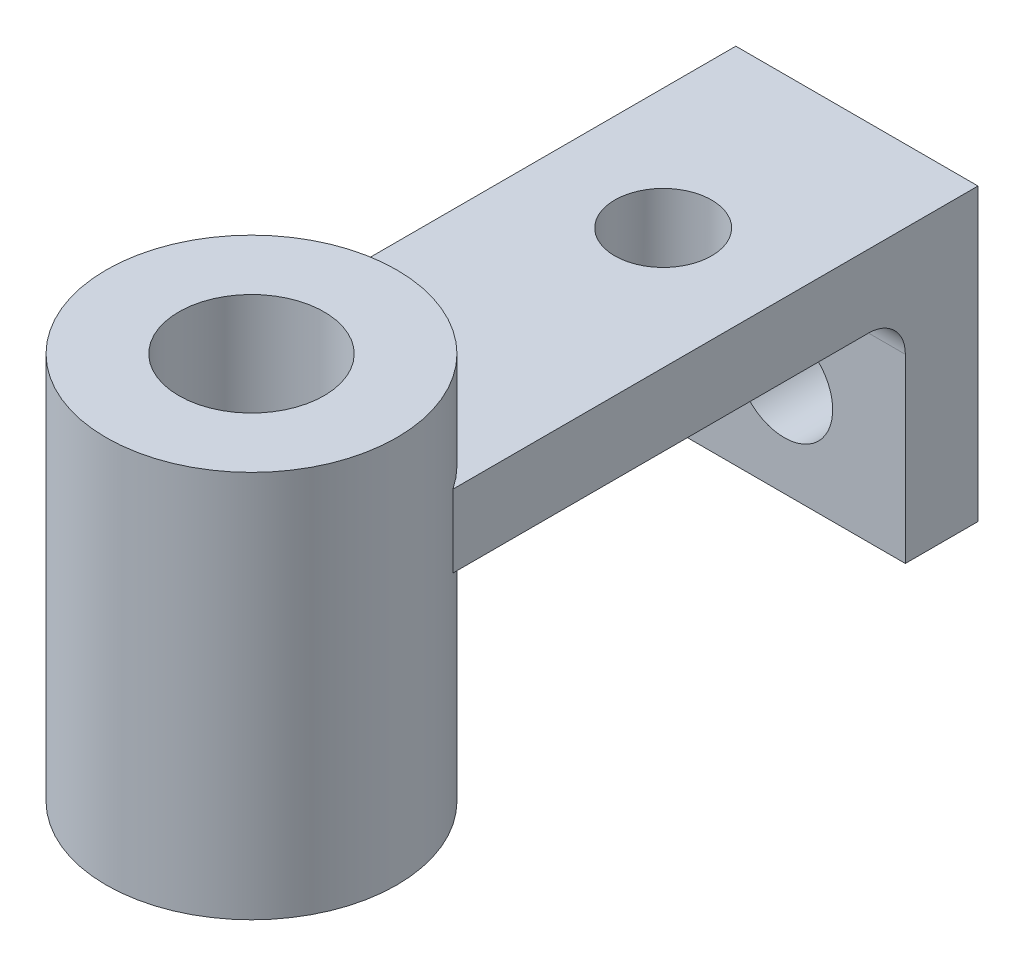
SolidWorks part; units mm, degrees
ref_plane "Alzado" through (0, 0, 0) normal (0, 0, 1) x (1, 0, 0)
ref_plane "Planta" through (0, 0, 0) normal (0, 1, 0) x (1, 0, 0)
ref_plane "Vista lateral" through (0, 0, 0) normal (1, 0, 0) x (0, 0, -1)
sketch "Croquis3" plane through (0, 0, 0) normal (1, 0, 0) x (0, 0, -1)
  line L0 (39.6875, 4.7625) -> (39.6875, -33.3375)
  line L1 (-39.6875, 4.7625) -> (39.6875, 4.7625)
  line L2 (-39.6875, 4.7625) -> (-39.6875, -4.7625)
  line L5 (-39.6875, 4.7625) -> (39.6875, -4.7625) construction
  line L6 (-39.6875, -4.7625) -> (39.6875, 4.7625) construction
  line L7 (39.6875, -33.3375) -> (30.1625, -33.3375)
  line L8 (30.1625, -33.3375) -> (30.1625, -9.5885)
  line L9 (25.3365, -4.7625) -> (-39.6875, -4.7625)
  arc A0 (30.1625, -9.5885) -> (25.3365, -4.7625) centre (25.3365, -9.5885) ccw
  point P0 (0, 0)
  dimension "D5" = 4.826
  dimension "D1" = 9.525
  dimension "D2" = 79.375
  dimension "D3" = 38.1
  dimension "D4" = 9.525
extrude "Saliente-Extruir1" add sketch "Croquis3" along normal blind 31.75 contours L9 L2 L1 L0 L7 L8 A0
sketch "Croquis5" plane through (0, 0, -39.6875) normal (0, 0, -1) x (-1, 0, 0)
  line L0 (-15.875, -16.1629) -> (-15.875, -35.7571) construction
  line L1 (-22.6938, -20.6375) -> (2.7786, -20.6375) construction
  line L2 (-31.75, -33.3375) -> (0, -33.3375) construction
  line L3 (0, 4.7625) -> (0, -33.3375) construction
  circle A0 centre (-15.875, -20.6375) radius 6.35
  dimension "D3" = 12.7
  dimension "D1" = 12.7
  dimension "D2" = 15.875
extrude "Cortar-Extruir1" cut sketch "Croquis5" against normal up to next
sketch "Croquis6" plane through (0, 4.7625, 0) normal (0, 1, 0) x (1, 0, 0)
  line L0 (31.75, -39.6875) -> (0, -39.6875) construction
  line L1 (0, -39.6875) -> (0, 39.6875) construction
  circle A0 centre (15.875, 14.2875) radius 6.35
  dimension "D3" = 12.7
  dimension "D1" = 53.975
  dimension "D2" = 15.875
extrude "Cortar-Extruir2" cut sketch "Croquis6" against normal up to next
sketch "Croquis7" plane through (0, 4.7625, 0) normal (0, 1, 0) x (1, 0, 0)
  line L0 (15.875, -43.3287) -> (15.875, 41.346) construction
  line L1 (31.75, -39.6875) -> (0, -39.6875) construction
  circle A0 centre (15.875, -39.6875) radius 19.05
  dimension "D1" = 38.1
extrude "Saliente-Extruir2" add sketch "Croquis7" along normal blind 12.7 and the other way blind 38.1
sketch "Croquis8" plane through (0, 17.4625, 0) normal (0, 1, 0) x (1, 0, 0)
  circle A0 centre (15.875, -39.6875) radius 9.525
  circle A1 centre (15.875, -39.6875) radius 19.05 construction
  dimension "D1" = 19.05
extrude "Cortar-Extruir3" cut sketch "Croquis8" against normal through all contours A0
